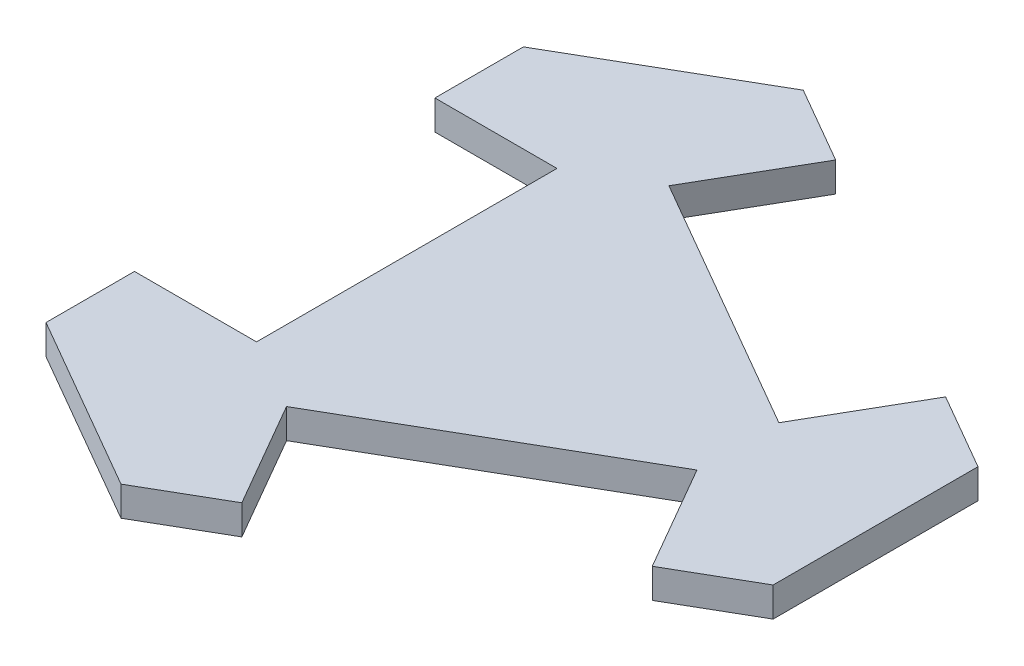
SolidWorks part; units mm, degrees
ref_plane "Front Plane" through (0, 0, 0) normal (0, 0, 1) x (1, 0, 0)
ref_plane "Top Plane" through (0, 0, 0) normal (0, 1, 0) x (1, 0, 0)
ref_plane "Right Plane" through (0, 0, 0) normal (1, 0, 0) x (0, 0, -1)
sketch "Sketch2" plane through (0, 0, 0) normal (0, 1, 0) x (1, 0, 0)
  line L0 (-86.6025, 80.718) -> (-26.6025, 115.359) construction
  line L1 (173.2051, 0) -> (-86.6025, 150) construction
  line L2 (-86.6025, 150) -> (-86.6025, -150) construction
  line L3 (-86.6025, -150) -> (173.2051, 0) construction
  line L4 (0, 0) -> (43.3013, -75) construction
  line L5 (0, 0) -> (43.3013, 75) construction
  line L6 (0, 0) -> (-86.6025, 0) construction
  line L7 (-86.6025, -80.718) -> (-26.6025, -115.359) construction
  line L8 (113.2051, -34.641) -> (113.2051, 34.641) construction
  line L9 (-26.6025, 115.359) -> (-86.6025, 80.718)
  line L11 (-86.6025, -80.718) -> (-26.6025, -115.359)
  line L13 (113.2051, -34.641) -> (113.2051, 34.641)
  line L15 (-21.3303, -64.6548) -> (-0.6928, -100.4)
  line L16 (-45.3275, -50.8) -> (-86.6025, -50.8)
  line L17 (-45.3275, -50.8) -> (-45.3275, 50.8)
  line L18 (-45.3275, 50.8) -> (-86.6025, 50.8)
  line L20 (-45.3275, -50.8) -> (-86.6025, 50.8) construction
  line L21 (-45.3275, 50.8) -> (-86.6025, -50.8) construction
  line L22 (-21.3303, -64.6548) -> (66.6579, -13.8548)
  line L23 (66.6579, -13.8548) -> (87.2954, -49.6)
  line L24 (66.6579, 13.8548) -> (87.2954, 49.6)
  line L25 (-21.3303, 64.6548) -> (-0.6928, 100.4)
  line L26 (66.6579, 13.8548) -> (-21.3303, 64.6548)
  line L27 (-86.6025, 80.718) -> (-86.6025, 50.8)
  line L28 (-86.6025, -80.718) -> (-86.6025, -50.8)
  line L29 (-26.6025, -115.359) -> (-0.6928, -100.4)
  line L30 (87.2954, -49.6) -> (113.2051, -34.641)
  line L31 (113.2051, 34.641) -> (87.2954, 49.6)
  line L32 (-0.6928, 100.4) -> (-26.6025, 115.359)
  circle A0 centre (0, 0) radius 86.6025 construction
  point P15 (25.9808, -85)
  point P16 (60.6218, -65)
  point P17 (60.6218, 65)
  point P18 (25.9808, 85)
  point P19 (-86.6025, 20)
  point P20 (-86.6025, -20)
  point P21 (-65.965, 0)
  dimension "D1" = 300
  dimension "D2" = 60
  dimension "D3" = 130
  dimension "D4" = 130
  dimension "D5" = 40
  dimension "D6" = 161.4359
  dimension "D7" = 101.6
  dimension "D8" = 41.275
extrude "Boss-Extrude1" add sketch "Sketch2" along normal blind 10
